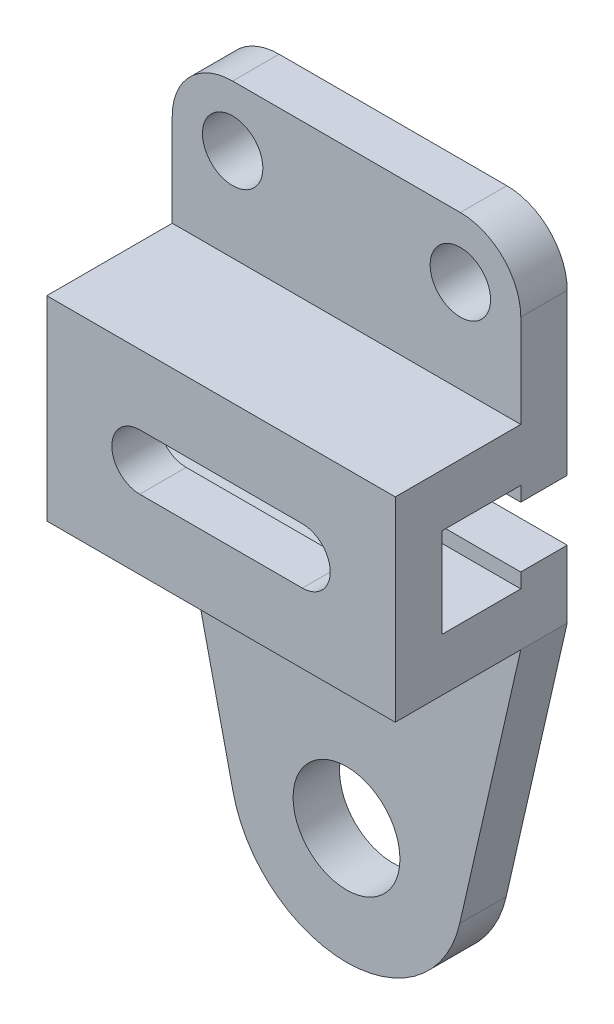
SolidWorks part; units mm, degrees
ref_plane "Front Plane" through (0, 0, 0) normal (0, 0, 1) x (1, 0, 0)
ref_plane "Top Plane" through (0, 0, 0) normal (0, 1, 0) x (1, 0, 0)
ref_plane "Right Plane" through (0, 0, 0) normal (1, 0, 0) x (0, 0, -1)
sketch "Sketch1" plane through (0, 0, 0) normal (1, 0, 0) x (0, 0, -1)
  line L0 (8.5, 21) -> (8.5, 54)
  line L1 (-18.5, -21) -> (8.5, -21)
  line L2 (-18.5, -21) -> (-18.5, 21)
  line L3 (-18.5, 21) -> (8.5, 21)
  line L4 (18.5, -21) -> (18.5, -6.5)
  line L5 (-18.5, -21) -> (18.5, 21) construction
  line L6 (-18.5, 21) -> (18.5, -21) construction
  line L7 (-8.5, -9.6486) -> (8.5, -9.6486)
  line L8 (-8.5, -9.6486) -> (-8.5, 9.6486)
  line L9 (-8.5, 9.6486) -> (8.5, 9.6486)
  line L10 (8.5, -9.6486) -> (8.5, -6.5)
  line L11 (-8.5, -9.6486) -> (8.5, 9.6486) construction
  line L12 (-8.5, 9.6486) -> (8.5, -9.6486) construction
  line L13 (8.5, 54) -> (18.5, 54)
  line L14 (18.5, 54) -> (18.5, 21)
  line L15 (18.5, -21) -> (18.5, -98)
  line L16 (18.5, -98) -> (8.5, -98)
  line L17 (8.5, -98) -> (8.5, -21)
  line L18 (8.5, -6.5) -> (18.5, -6.5)
  line L19 (8.5, 6.5) -> (18.5, 6.5)
  line L20 (-23.3759, 0) -> (-12.0423, 0) construction
  line L21 (18.5, 6.5) -> (18.5, 21)
  line L22 (8.5, 6.5) -> (8.5, 9.6486)
  point P0 (0, 0)
  point P5 (0, 0)
  point P13 (0, 0)
  point P22 (0, 0)
  dimension "D1" = 42
  dimension "D2" = 10
  dimension "D3" = 13
  dimension "D4" = 10
  dimension "D5" = 37
  dimension "D6" = 33
  dimension "D7" = 152
extrude "Boss-Extrude1" add sketch "Sketch1" along normal mid plane 75
sketch "Sketch2" plane through (0, 0, 0) normal (0, 0, 1) x (1, 0, 0)
  line L0 (-17.5, 0) -> (17.5, 0) construction
  line L1 (-17.5, 6) -> (17.5, 6)
  line L2 (-17.5, -6) -> (17.5, -6)
  line L3 (37.5, -21) -> (24.3743, -78.5584)
  line L4 (-37.5, -21) -> (-24.3743, -78.5584)
  line L5 (0, 73.3987) -> (0, -122.1422) construction
  line L6 (37.5, -98) -> (-37.5, -98) construction
  line L7 (37.5, 54) -> (37.5, 21) construction
  line L8 (37.5, 54) -> (-37.5, 54) construction
  line L9 (-37.5, 41) -> (-37.5, 54)
  line L10 (-37.5, 54) -> (37.5, 54)
  line L11 (37.5, 54) -> (37.5, 41)
  line L12 (37.5, -21) -> (37.5, -98)
  line L13 (37.5, -98) -> (-37.5, -98)
  line L14 (-37.5, -98) -> (-37.5, -21)
  circle A0 centre (0, -73) radius 11.5
  arc A1 (-24.3743, -78.5584) -> (24.3743, -78.5584) centre (0, -73) ccw
  circle A2 centre (24.5, 41) radius 6.5
  arc A3 (37.5, 41) -> (24.5, 54) centre (24.5, 41) ccw
  arc A6 (-17.5, 6) -> (-17.5, -6) centre (-17.5, 0) ccw
  arc A7 (17.5, -6) -> (17.5, 6) centre (17.5, 0) ccw
  arc A8 (-37.5, 41) -> (-24.5, 54) centre (-24.5, 41) cw
  circle A9 centre (-24.5, 41) radius 6.5
  point P12 (0, 0)
  dimension "D1" = 50
  dimension "D2" = 23
  dimension "D3" = 6
  dimension "D5" = 26
  dimension "D6" = 13
  dimension "D4" = 35
extrude "Cut-Extrude1" cut sketch "Sketch2" against normal through all both and the other way through all contours A1 L13 L12 L3 | A0 | A1 L4 L14 L13 | L2 A7 L1 A6 | A2 | A9 | A3 L11 L10 | L9 A8 L10
